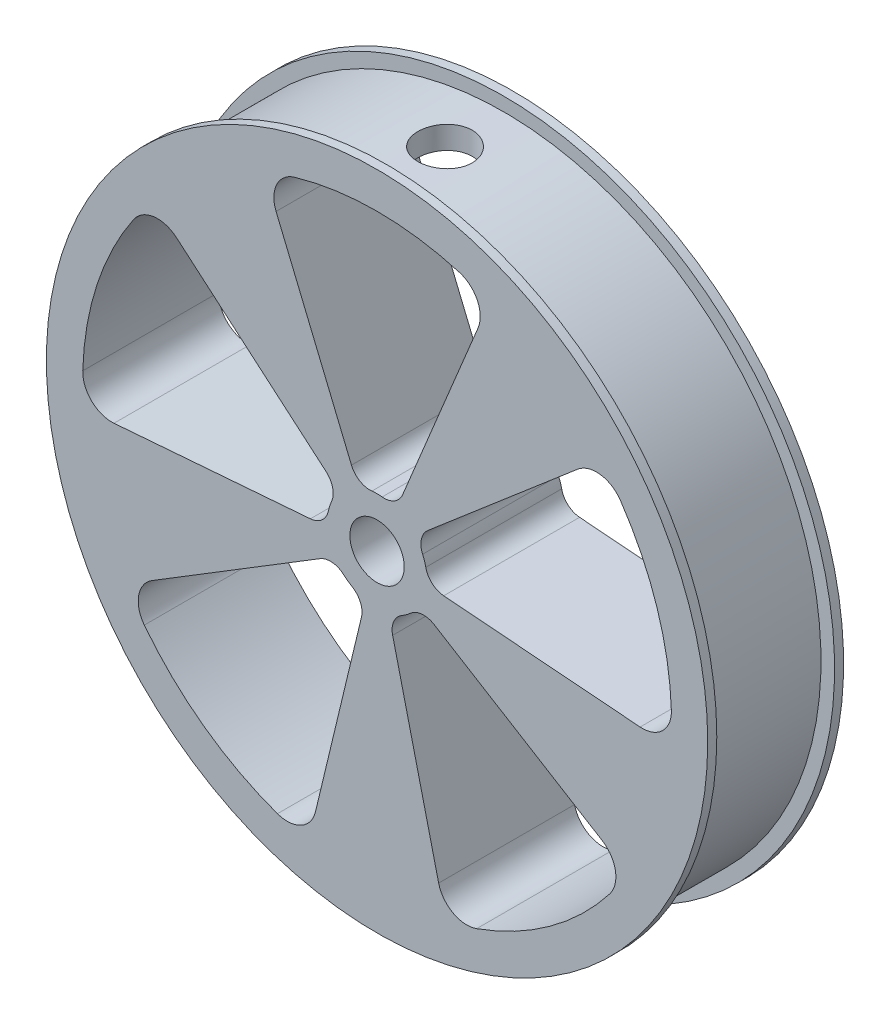
SolidWorks part; units mm, degrees
material "PA Type 6"
ref_plane "Front Plane" through (0, 0, 0) normal (0, 0, 1) x (1, 0, 0)
ref_plane "Top Plane" through (0, 0, 0) normal (0, 1, 0) x (1, 0, 0)
ref_plane "Right Plane" through (0, 0, 0) normal (1, 0, 0) x (0, 0, -1)
sketch "Sketch1" plane through (0, 0, 0) normal (0, 0, 1) x (1, 0, 0)
  circle A0 centre (0, 0) radius 35
  dimension "D1" = 70
extrude "Boss-Extrude1" add sketch "Sketch1" along normal blind 15
sketch "Sketch2" plane through (0, 0, 0) normal (0, 0, -1) x (-1, 0, 0)
  circle A0 centre (0, 0) radius 3
  dimension "D1" = 6
extrude "Cut-Extrude1" cut sketch "Sketch2" against normal through all
sketch "Sketch4" plane through (0, 0, 0) normal (0, 0, -1) x (-1, 0, 0)
  line L1 (2.1048, 5.0813) -> (12.4372, 30.0261)
  line L15 (-2.1048, 5.0813) -> (-12.4372, 30.0261)
  arc A0 (2.1048, 5.0813) -> (-2.1048, 5.0813) centre (0, 0) ccw
  arc A1 (12.4372, 30.0261) -> (-12.4372, 30.0261) centre (0, 0) ccw
  point P39 (0, 0)
  dimension "D1" = 11
  dimension "D3" = 65
extrude "Cut-Extrude3" cut sketch "Sketch4" against normal through all contours L1 A1 L15 A0
pattern_circular "CirPattern1" count 5 over 360 about axis through (0, 0, 0) along (0, 0, 1) of "Cut-Extrude3"
fillet "Fillet4" radius 2.2 10 edges at (-2.1048, 5.0813, 7.5) (2.1048, 5.0813, 7.5) (1.2839, -5.348, 7.5) (4.6895, -2.8737, 7.5) (-4.6895, -2.8737, 7.5) (-1.2839, -5.348, 7.5) (-5.483, -0.4315, 7.5) (-4.1822, 3.572, 7.5) (4.1822, 3.572, 7.5) (5.483, -0.4315, 7.5)
fillet "Fillet5" radius 3.2 10 edges at (-27.7108, -16.9812, 7.5) (-7.587, -31.602, 7.5) (7.587, -31.602, 7.5) (27.7108, -16.9812, 7.5) (32.3998, -2.5499, 7.5) (24.7132, 21.1071, 7.5) (12.4372, 30.0261, 7.5) (-12.4372, 30.0261, 7.5) (-24.7132, 21.1071, 7.5) (-32.3998, -2.5499, 7.5)
sketch "Sketch5" plane through (0, 0, 0) normal (0, 0, -1) x (-1, 0, 0)
  circle A0 centre (0, 0) radius 35
  circle A1 centre (0, 0) radius 36.5
  dimension "D1" = 73
  dimension "D2" = 70
extrude "Boss-Extrude2" add sketch "Sketch5" against normal blind 1
sketch "Sketch6" plane through (0, 0, 15) normal (0, 0, 1) x (1, 0, 0)
  circle A0 centre (0, 0) radius 35
  circle A1 centre (0, 0) radius 36.5
  dimension "D1" = 73
  dimension "D2" = 70
extrude "Boss-Extrude3" add sketch "Sketch6" against normal blind 1
sketch "Sketch7" plane through (0, 0, 0) normal (0, 1, 0) x (1, 0, 0)
  line L0 (0, 0) -> (0, -7.5)
  circle A0 centre (0, -7.5) radius 1.55
  dimension "D2" = 3.1
  dimension "D1" = 7.5
extrude "Cut-Extrude4" cut sketch "Sketch7" along normal through all contours A0
sketch "Sketch8" plane through (0, 0, 0) normal (0, 1, 0) x (1, 0, 0)
  circle A0 centre (0, -7.5) radius 3
  dimension "D1" = 6
extrude "Cut-Extrude5" cut sketch "Sketch8" against normal blind 1 and the other way through all from offset 20 contours A0
